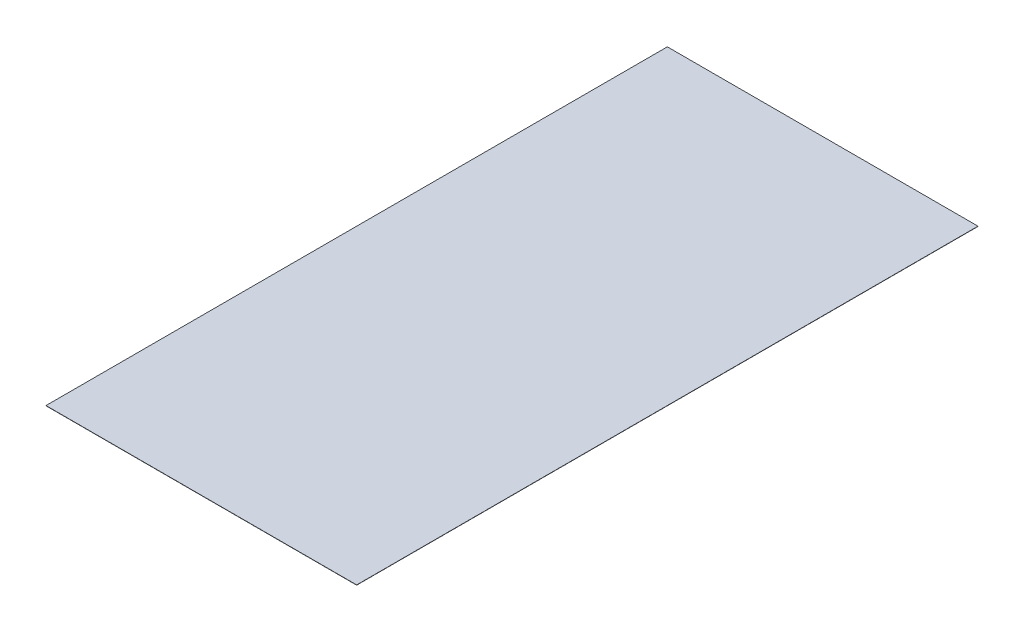
SolidWorks part; units mm, degrees
ref_plane "Front Plane" through (0, 0, 0) normal (0, 0, 1) x (1, 0, 0)
ref_plane "Top Plane" through (0, 0, 0) normal (0, 1, 0) x (1, 0, 0)
ref_plane "Right Plane" through (0, 0, 0) normal (1, 0, 0) x (0, 0, -1)
sketch "Sketch1" plane through (0, 0, 0) normal (0, 1, 0) x (1, 0, 0)
  line L1 (-609.6, 1219.2) -> (609.6, 1219.2)
  line L2 (-609.6, 1219.2) -> (-609.6, -1219.2)
  line L3 (-609.6, -1219.2) -> (609.6, -1219.2)
  line L4 (609.6, 1219.2) -> (609.6, -1219.2)
  line L5 (-609.6, 1219.2) -> (609.6, -1219.2) construction
  line L6 (-609.6, -1219.2) -> (609.6, 1219.2) construction
  point P0 (0, 0)
  dimension "D1" = 2438.4
  dimension "D2" = 1219.2
extrude "Boss-Extrude1" add sketch "Sketch1" along normal blind 0.912
